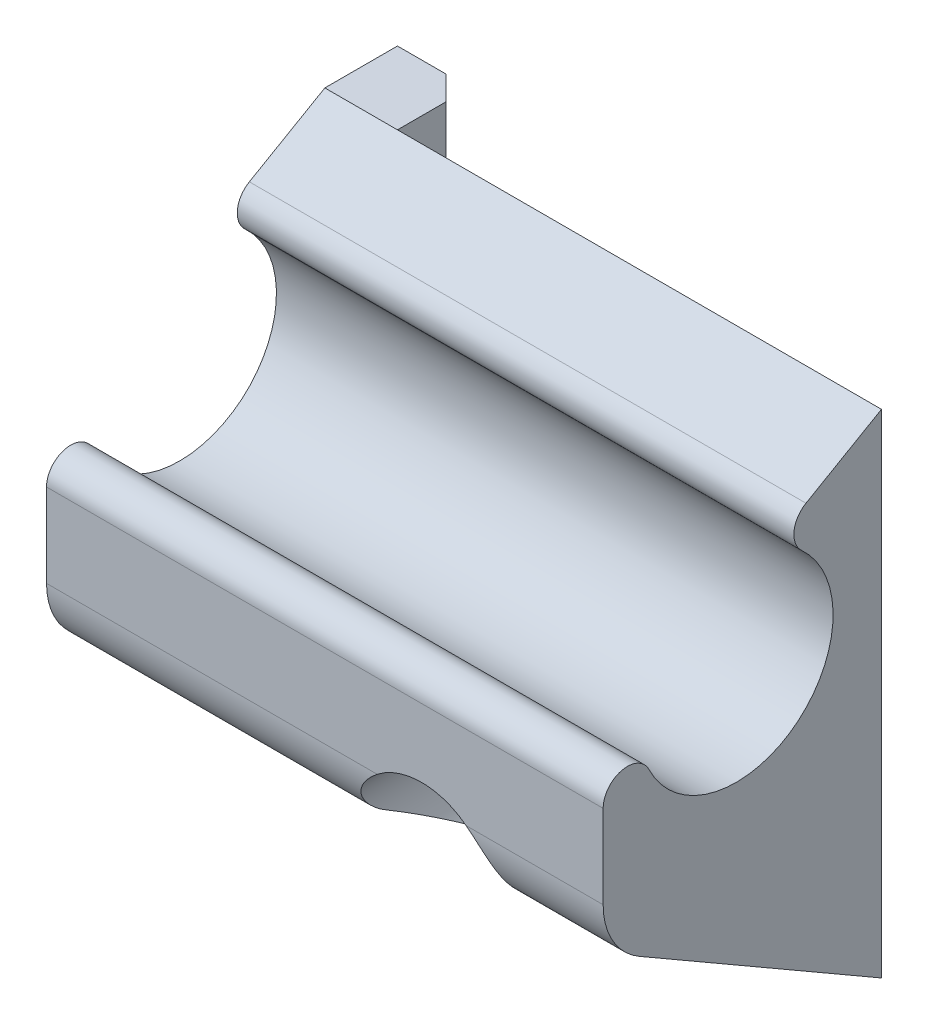
SolidWorks part; units mm, degrees
ref_plane "前视基准面" through (0, 0, 0) normal (0, 0, 1) x (1, 0, 0)
ref_plane "上视基准面" through (0, 0, 0) normal (0, 1, 0) x (1, 0, 0)
ref_plane "右视基准面" through (0, 0, 0) normal (1, 0, 0) x (0, 0, -1)
sketch "草图1" plane through (0, 0, 0) normal (1, 0, 0) x (0, 0, -1)
  line L0 (0, 0) -> (0, 14.3509)
  line L1 (0, 14.3509) -> (-3.1193, 12.5499)
  line L2 (0, 0) -> (0, -6)
  line L3 (0, -6) -> (-11.5, 0.6395)
  line L4 (-11.5, 0.6395) -> (-11.5, 5.8206)
  line L6 (0, 0) -> (-11.5, 0) construction
  arc A0 (-9.6, 6.2564) -> (-3.2955, 10.9471) centre (-6, 8) ccw
  arc A1 (-9.6, 6.2564) -> (-11.5, 5.8206) centre (-10.5, 5.8206) ccw
  arc A2 (-3.1193, 12.5499) -> (-3.2955, 10.9471) centre (-2.6193, 11.6839) ccw
  dimension "D1" = 8
  dimension "D2" = 8
  dimension "D4" = 6
  dimension "D5" = 5.5
  dimension "D6" = 1
  dimension "D7" = 1
  dimension "D3" = 2.5
  dimension "D8" = 60
  dimension "D9" = 6
  dimension "D10" = 60
extrude "凸台-拉伸1" add sketch "草图1" along normal blind 7.5 and the other way blind 15.5
sketch "草图2" plane through (0, 0, 11.5) normal (0, 0, 1) x (1, 0, 0)
  circle A0 centre (0, 0) radius 1.6
  dimension "D1" = 3.2
extrude "切除-拉伸1" cut sketch "草图2" against normal through all
sketch "草图3" plane through (0, 0, 11.5) normal (0, 0, 1) x (1, 0, 0)
  circle A0 centre (0, 0) radius 3
  dimension "D1" = 6
extrude "切除-拉伸2" cut sketch "草图3" against normal blind 6
sketch "草图4" plane through (0, 0, 0) normal (0, 0, -1) x (-1, 0, 0)
  line L0 (15.5, -6) -> (-7.5, -6) construction
  line L1 (15.5, 14.3509) -> (12.5, 14.3509)
  line L2 (15.5, 14.3509) -> (15.5, -6)
  line L3 (15.5, -6) -> (12.5, -6)
  line L4 (12.5, 14.3509) -> (12.5, -6)
  dimension "D1" = 3
extrude "凸台-拉伸2" add sketch "草图4" along normal blind 3
fillet "圆角1" radius 3 2 edges at (5.2155, 0.6395, 11.5) (-9.2155, 0.6395, 11.5)
chamfer "倒角2" distance 1 angle 45 1 edges at (-12.5, 4.1754, -3)
